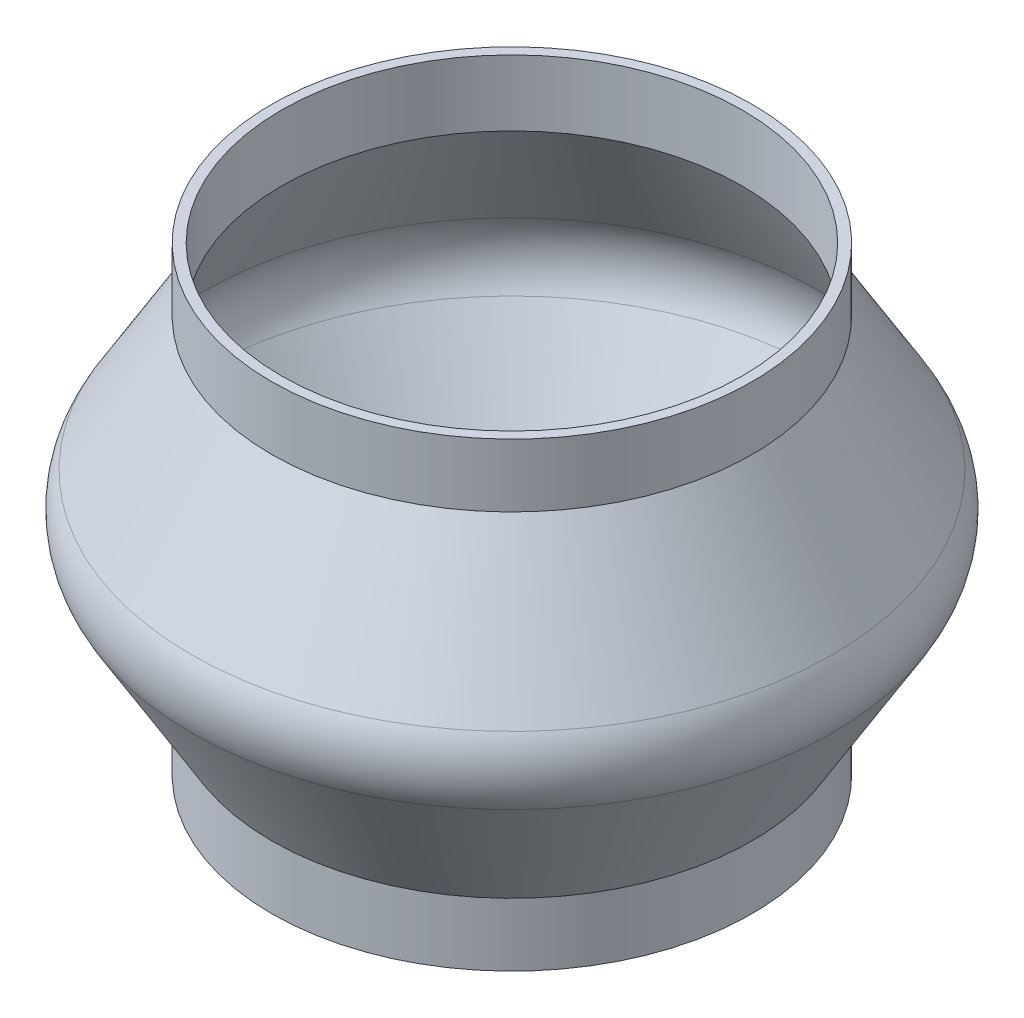
SolidWorks part; units mm, degrees
ref_plane "Front Plane" through (0, 0, 0) normal (0, 0, 1) x (1, 0, 0)
ref_plane "Top Plane" through (0, 0, 0) normal (0, 1, 0) x (1, 0, 0)
ref_plane "Right Plane" through (0, 0, 0) normal (1, 0, 0) x (0, 0, -1)
sketch "Sketch1" plane through (0, 0, 0) normal (0, 0, 1) x (1, 0, 0)
  line L0 (0, 85.8261) -> (0, -77) construction
  line L1 (-78.8261, 0) -> (77.6087, 0) construction
  line L2 (-35, 35) -> (-35, 25)
  line L3 (-35, 25) -> (-46.913, 5.145)
  line L4 (-36.5, 35) -> (-36.5, 25.4155)
  line L5 (-36.5, 25.4155) -> (-48.6623, 5.145)
  line L6 (-36.5, 25.4155) -> (-51.2862, 0.7717) construction
  line L7 (-36.5, 35) -> (-35, 35)
  line L8 (-36.5, -25.4155) -> (-48.6623, -5.145)
  line L9 (-36.5, -35) -> (-36.5, -25.4155)
  line L10 (-35, -25) -> (-46.913, -5.145)
  line L11 (-35, -35) -> (-35, -25)
  line L12 (-36.5, -35) -> (-35, -35)
  line L13 (-35, 25) -> (-50, 0) construction
  arc A0 (-48.6623, -5.145) -> (-48.6623, 5.145) centre (-40.0874, 0) cw
  arc A1 (-46.913, -5.145) -> (-46.913, 5.145) centre (-38.3381, 0) cw
  point P18 (-51.7493, 0)
  point P22 (-50, 0)
  dimension "D6" = 10
  dimension "D1" = 35
  dimension "D2" = 50
  dimension "D3" = 10
  dimension "D4" = 25
  dimension "D5" = 1.5
revolve "Revolve1" add sketch "Sketch1" angle 360 about L0
